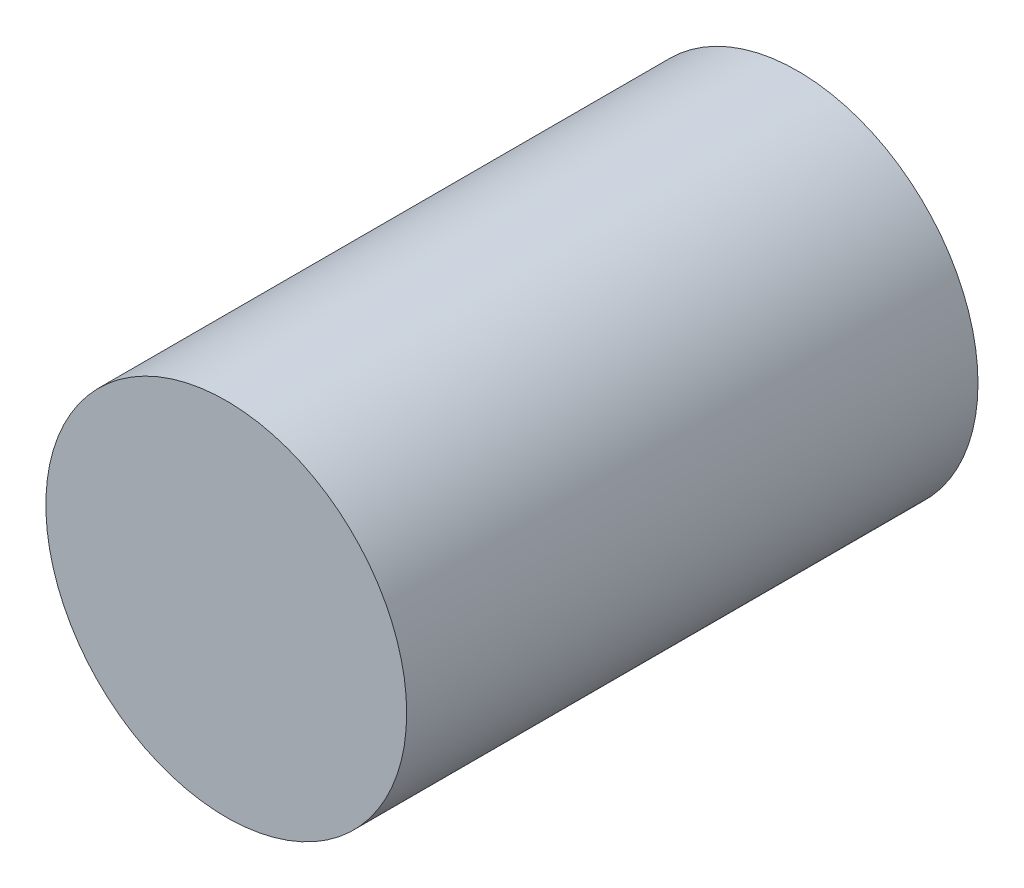
SolidWorks part; units mm, degrees
ref_plane "前视基准面" through (0, 0, 0) normal (0, 0, 1) x (1, 0, 0)
ref_plane "上视基准面" through (0, 0, 0) normal (0, 1, 0) x (1, 0, 0)
ref_plane "右视基准面" through (0, 0, 0) normal (1, 0, 0) x (0, 0, -1)
other "Configuration Table"
sketch "草图1" plane through (0, 0, 0) normal (0, 0, 1) x (1, 0, 0)
  circle A0 centre (0, 0) radius 3
  dimension "diameter" = 6
extrude "Cable_envelope" add sketch "草图1" along normal blind 9.5
